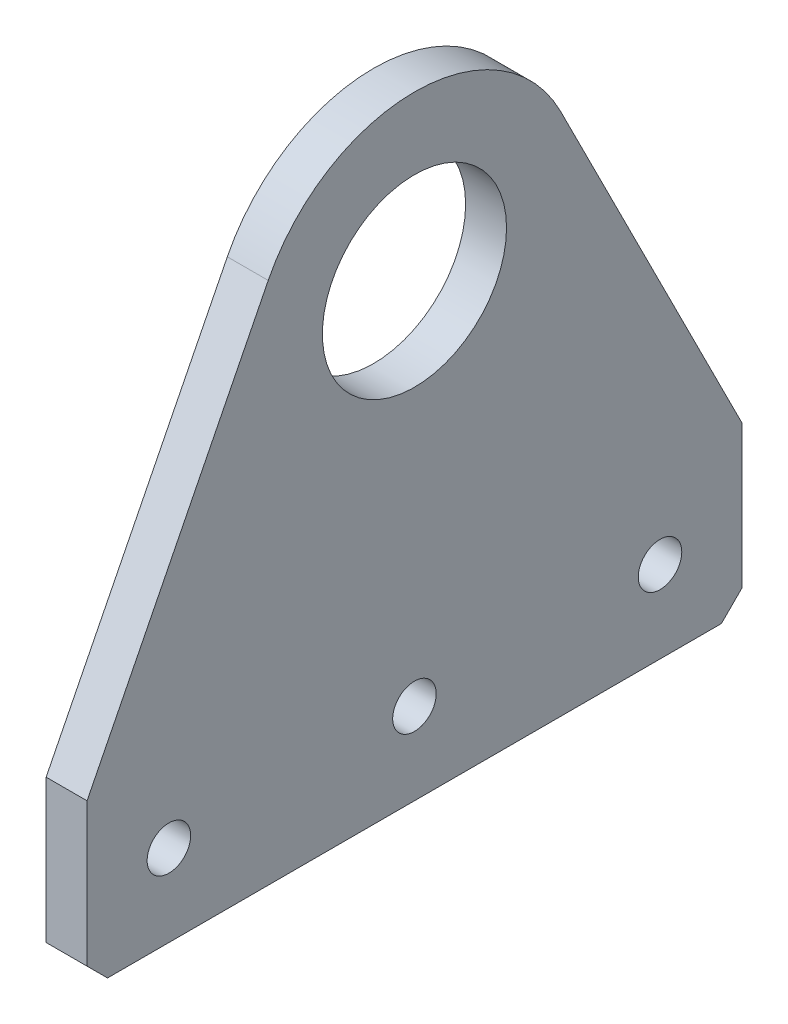
SolidWorks part; units mm, degrees
material "6061-T6 (SS)"
ref_plane "Front Plane" through (0, 0, 0) normal (0, 0, 1) x (1, 0, 0)
ref_plane "Top Plane" through (0, 0, 0) normal (0, 1, 0) x (1, 0, 0)
ref_plane "Right Plane" through (0, 0, 0) normal (1, 0, 0) x (0, 0, -1)
sketch "Sketch1" plane through (0, 0, 0) normal (1, 0, 0) x (0, 0, -1)
  line L0 (0, 0) -> (0, 25.4)
  line L1 (0, 25.4) -> (28.1104, 81.2667)
  line L2 (73.4896, 81.2667) -> (101.6, 25.4)
  line L3 (101.6, 25.4) -> (101.6, 0)
  line L4 (101.6, 0) -> (0, 0)
  arc A0 (28.1104, 81.2667) -> (73.4896, 81.2667) centre (50.8, 69.85) cw
  circle A1 centre (50.8, 69.85) radius 14.2875
  dimension "D3" = 28.575
  dimension "D4" = 25.4
  dimension "D5" = 69.85
  dimension "D1" = 101.6
  dimension "D2" = 25.4
extrude "Boss-Extrude1" add sketch "Sketch1" along normal blind 6.35
sketch "Sketch2" plane through (6.35, 0, 0) normal (1, 0, 0) x (0, 0, -1)
  line L0 (0, 25.4) -> (0, 0) construction
  line L1 (101.6, 0) -> (101.6, 25.4) construction
  line L2 (0, 0) -> (101.6, 0) construction
  line L3 (12.7, 12.7) -> (88.9, 12.7) construction
  circle A0 centre (12.7, 12.7) radius 3.3782
  circle A1 centre (50.8, 12.7) radius 3.3782
  circle A2 centre (88.9, 12.7) radius 3.3782
  point P6 (0, 0)
  point P13 (88.0039, 12.7)
  dimension "D1" = 12.7
  dimension "D2" = 12.7
  dimension "D3" = 12.7
  dimension "D4" = 6.7564
extrude "Cut-Extrude1" cut sketch "Sketch2" against normal through all
chamfer "Chamfer1" distance 3.175 angle 45 2 edges at (3.175, 0, -101.6) (3.175, 0, 0)
